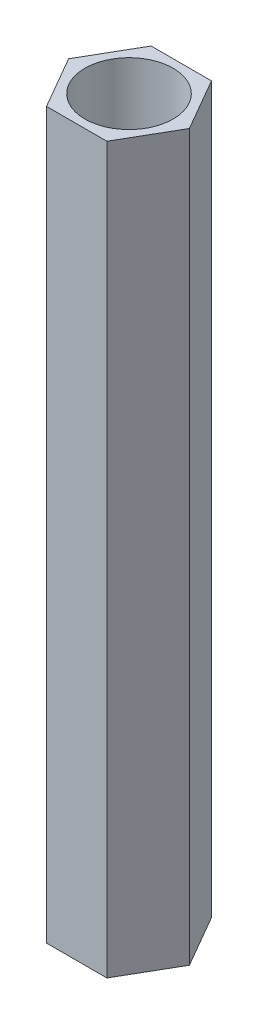
SolidWorks part; units mm, degrees
ref_plane "Alzado" through (0, 0, 0) normal (0, 0, 1) x (1, 0, 0)
ref_plane "Planta" through (0, 0, 0) normal (0, 1, 0) x (1, 0, 0)
ref_plane "Vista lateral" through (0, 0, 0) normal (1, 0, 0) x (0, 0, -1)
sketch "Croquis1" plane through (0, 0, 0) normal (0, 1, 0) x (1, 0, 0)
  line L1 (2.5, 0) -> (1.25, 2.1651)
  line L2 (1.25, 2.1651) -> (-1.25, 2.1651)
  line L3 (-1.25, 2.1651) -> (-2.5, 0)
  line L4 (-2.5, 0) -> (-1.25, -2.1651)
  line L5 (-1.25, -2.1651) -> (1.25, -2.1651)
  line L6 (1.25, -2.1651) -> (2.5, 0)
  circle A2 centre (0, 0) radius 2.1651 construction
  circle A3 centre (0, 0) radius 1.825
  dimension "D1" = 5
  dimension "D2" = 3.65
extrude "Saliente-Extruir1" add sketch "Croquis1" along normal blind 30
